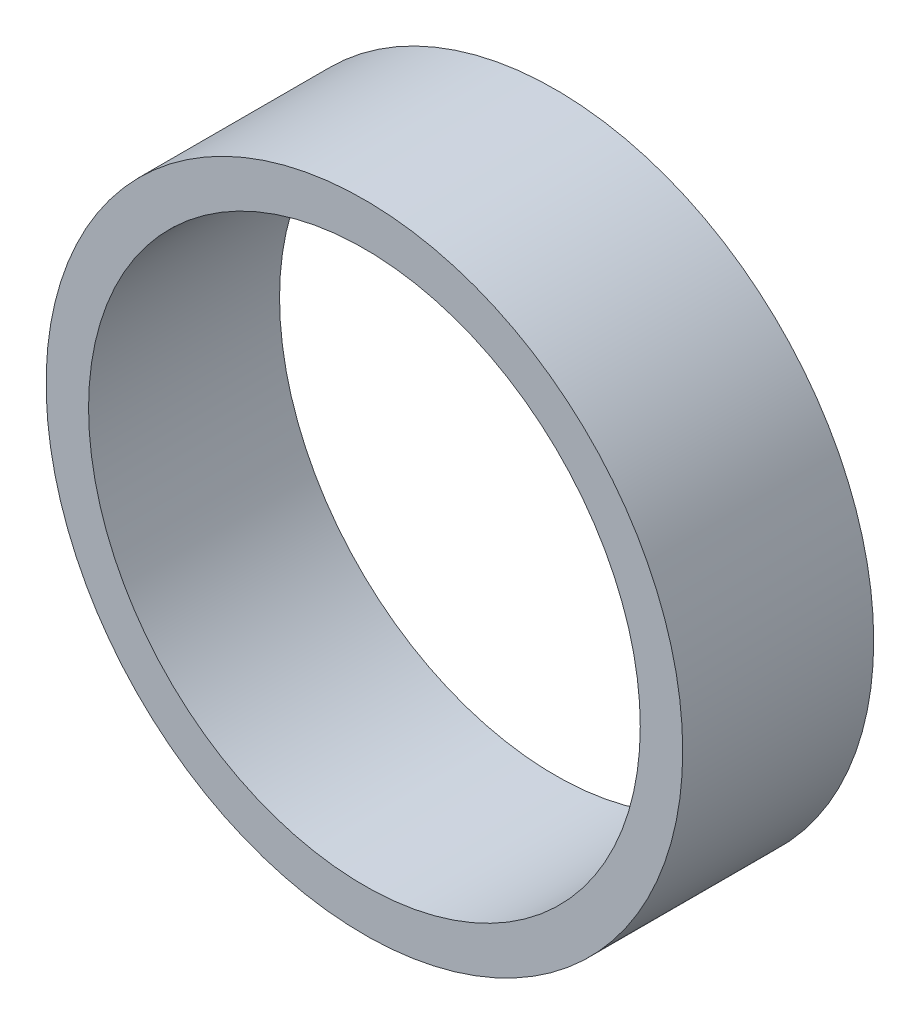
SolidWorks part; units mm, degrees
material "NBR"
ref_plane "Front Plane" through (0, 0, 0) normal (0, 0, 1) x (1, 0, 0)
ref_plane "Top Plane" through (0, 0, 0) normal (0, 1, 0) x (1, 0, 0)
ref_plane "Right Plane" through (0, 0, 0) normal (1, 0, 0) x (0, 0, -1)
sketch "Sketch1" plane through (0, 0, 0) normal (0, 0, 1) x (1, 0, 0)
  circle A0 centre (0, 0) radius 38.1
  circle A1 centre (0, 0) radius 33.02
  dimension "D1" = 76.2
  dimension "D2" = 5.08
extrude "Boss-Extrude1" add sketch "Sketch1" along normal blind 22.86
